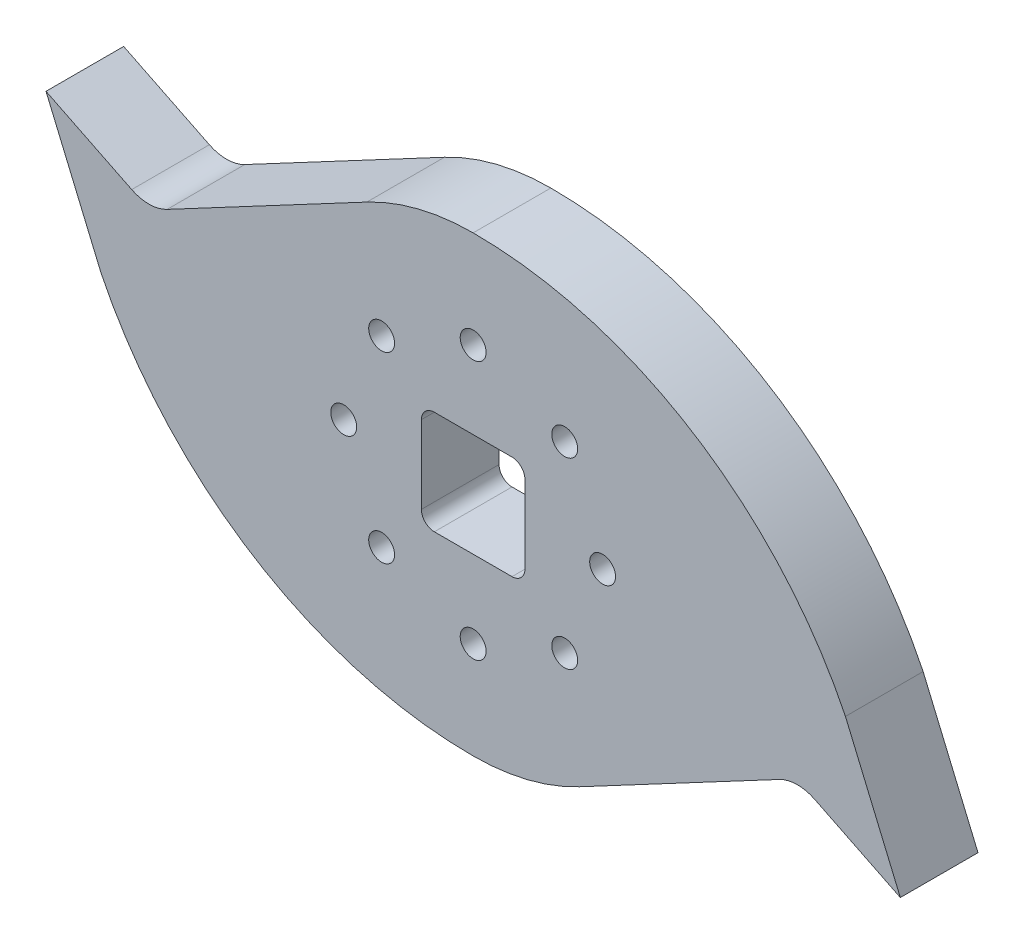
SolidWorks part; units mm, degrees
ref_plane "前视基准面" through (0, 0, 0) normal (0, 0, 1) x (1, 0, 0)
ref_plane "上视基准面" through (0, 0, 0) normal (0, 1, 0) x (1, 0, 0)
ref_plane "右视基准面" through (0, 0, 0) normal (1, 0, 0) x (0, 0, -1)
sketch "草图1" plane through (0, 0, 0) normal (0, 0, 1) x (1, 0, 0)
  line L1 (-3, -4) -> (3, -4)
  line L2 (-4, -3) -> (-4, 3)
  line L3 (-3, 4) -> (3, 4)
  line L4 (4, -3) -> (4, 3)
  line L5 (-4, -4) -> (4, 4) construction
  line L6 (-4, 4) -> (4, -4) construction
  line L7 (0, 30.4831) -> (0, -36.3778) construction
  line L8 (-15.248, -14.5) -> (-9.798, -14.5) construction
  line L10 (-4.0079, 17.6889) -> (-2.6765, 17.2941) construction
  line L12 (-8.2158, 15.4516) -> (-11.1659, 21) construction
  line L13 (0, 0) -> (24.8597, -46.7542) construction
  line L14 (8.2158, -15.4516) -> (23.6433, -7.2486)
  line L16 (28.7607, -0.4707) -> (33, -10.4707)
  line L19 (33, -10.4707) -> (26.3782, -7.2066)
  line L21 (-17.173, 10.6889) -> (-4.0079, 17.6889) construction
  line L22 (-4.0079, 17.6889) -> (-8.2158, 15.4516) construction
  line L23 (-17.173, 10.6889) -> (-13.1652, 11.5294) construction
  line L27 (-13.1652, 11.5294) -> (-7.4439, 14) construction
  line L30 (-21.4783, 40.3948) -> (-8.2158, 15.4516) construction
  line L31 (-11.1659, 21) -> (0, 21) construction
  line L32 (-11.1659, 21) -> (-7.4439, 14) construction
  line L33 (-7.4439, 14) -> (0, 0) construction
  line L38 (-9.798, -14.5) -> (0, -14.5) construction
  line L40 (-28.7607, 0.4707) -> (-33, 10.4707)
  line L41 (-33, 10.4707) -> (-26.3782, 7.2066)
  line L42 (-8.2158, 15.4516) -> (-23.6433, 7.2486)
  arc A0 (3, -4) -> (4, -3) centre (3, -3) ccw
  arc A1 (4, 3) -> (3, 4) centre (3, 3) ccw
  arc A2 (-4, -3) -> (-3, -4) centre (-3, -3) ccw
  arc A3 (-4, 3) -> (-3, 4) centre (-3, 3) cw
  arc A4 (-13.1652, -11.5294) -> (-9.798, -14.5) centre (0, 0) ccw construction
  arc A5 (0, 17.5) -> (28.7607, -0.4707) centre (0, -14.5) cw
  arc A6 (0, -17.5) -> (-15.248, -14.5) centre (0, 22.75) cw construction
  arc A8 (23.6433, -7.2486) -> (26.3782, -7.2066) centre (25.0518, -9.8974) cw
  arc A9 (-8.2158, 15.4516) -> (0, 17.5) centre (0, 0) cw construction
  arc A10 (0, -17.5) -> (8.2158, -15.4516) centre (0, 0) ccw
  arc A11 (-13.1652, 11.5294) -> (-17.5, 0) centre (0, 0) ccw construction
  arc A12 (-8.2158, 15.4516) -> (-2.6765, 17.2941) centre (0, 0) ccw construction
  arc A13 (-2.6765, 17.2941) -> (-13.1652, 11.5294) centre (0, 0) ccw construction
  arc A14 (0, 17.5) -> (-8.2158, 15.4516) centre (0, 0) ccw construction
  arc A15 (-17.5, 0) -> (-13.1652, -11.5294) centre (0, 0) ccw construction
  arc A16 (-15.248, -14.5) -> (-23.0448, -10.25) centre (0, 22.75) cw construction
  arc A18 (-9.798, -14.5) -> (0, -17.5) centre (0, 0) ccw construction
  arc A19 (0, -17.5) -> (0, 17.5) centre (0, 0) ccw construction
  arc A20 (0, -17.5) -> (-28.7607, 0.4707) centre (0, 14.5) cw
  arc A21 (-23.6433, 7.2486) -> (-26.3782, 7.2066) centre (-25.0518, 9.8974) cw
  arc A22 (0, 17.5) -> (-8.2158, 15.4516) centre (0, 0) ccw
  point P0 (0, 0)
  point P55 (-34.026, 5.9752)
  point P58 (25, -6.5272)
  point P77 (0, 0)
  dimension "D3" = 1
  dimension "D4" = 35
  dimension "D14" = 3
  dimension "D6" = 32
  dimension "D1" = 8
  dimension "D2" = 8
  dimension "D5" = 10
  dimension "D7" = 28
  dimension "D8" = 28
  dimension "D9" = 25
  dimension "D10" = 8
  dimension "D15" = 2
extrude "凸台-拉伸1" add sketch "草图1" along normal blind 6
sketch "草图2" plane through (0, 0, 6) normal (0, 0, 1) x (1, 0, 0)
  circle A0 centre (0, 10) radius 1
  circle A1 centre (7.0711, 7.0711) radius 1
  circle A2 centre (10, 0) radius 1
  circle A3 centre (7.0711, -7.0711) radius 1
  circle A4 centre (0, -10) radius 1
  circle A5 centre (-7.0711, -7.0711) radius 1
  circle A6 centre (-10, 0) radius 1
  circle A7 centre (-7.0711, 7.0711) radius 1
  point P20 (0, 0)
  dimension "D1" = 2
  dimension "D2" = 10
  dimension "D3" = 8
extrude "切除-拉伸1" cut sketch "草图2" against normal through all
